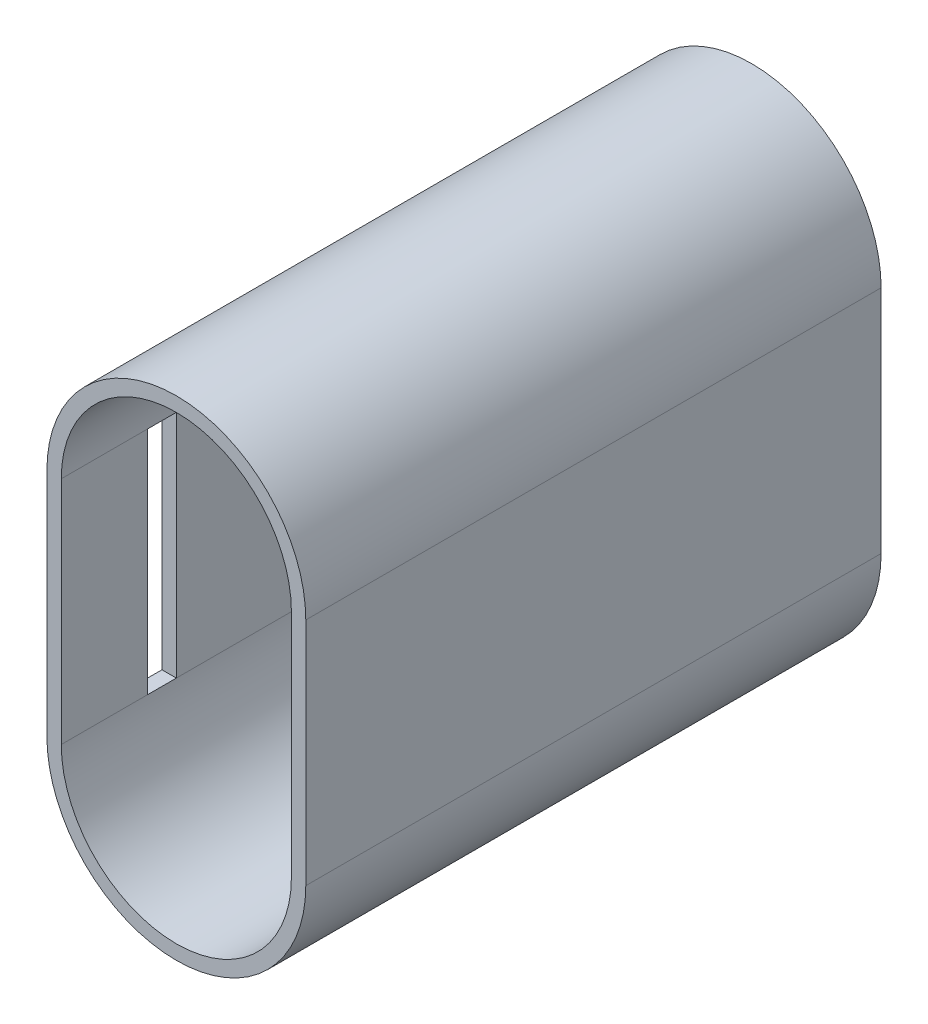
SolidWorks part; units mm, degrees
material "AISI 316 Нержавеющая сталь, лист (SS)"
ref_plane "Спереди" through (0, 0, 0) normal (0, 0, 1) x (1, 0, 0)
ref_plane "Сверху" through (0, 0, 0) normal (0, 1, 0) x (1, 0, 0)
ref_plane "Справа" through (0, 0, 0) normal (1, 0, 0) x (0, 0, -1)
other "Configuration Table"
sketch "Эскиз1" plane through (0, 0, 0) normal (0, 0, 1) x (1, 0, 0)
  line L0 (0, -40) -> (0, 40) construction
  line L1 (-45, -40) -> (-45, 40)
  line L2 (-40, -40) -> (-40, 40)
  line L3 (40, -40) -> (40, 40)
  line L4 (45, -40) -> (45, 40)
  arc A0 (-40, -40) -> (40, -40) centre (0, -40) ccw
  arc A1 (40, 40) -> (-40, 40) centre (0, 40) ccw
  arc A2 (45, 40) -> (-45, 40) centre (0, 40) ccw
  arc A3 (-45, -40) -> (45, -40) centre (0, -40) ccw
  point P3 (0, 80)
  point P4 (0, -80)
  point P5 (0, 0)
  dimension "D2" = 80
  dimension "D1" = 160
  dimension "D3" = 5
extrude "длина_камеры" add sketch "Эскиз1" along normal blind 200
sketch "Эскиз2" plane through (-45, 0, 0) normal (-1, 0, 0) x (0, 0, 1)
  line L0 (100, 40) -> (100, -40) construction
  line L1 (200, 40) -> (0, 40) construction
  line L2 (200, -40) -> (0, -40) construction
  line L4 (43, 40) -> (30, 40)
  line L5 (43, 40) -> (43, -40)
  line L6 (43, -40) -> (30, -40)
  line L7 (30, 40) -> (30, -40)
  line M6 (0, -40) -> (200, -40)
  line M8 (200, 40) -> (0, 40)
  dimension "D1" = 13
  dimension "D2" = 70
extrude "выпуск" cut sketch "Эскиз2" against normal up to surface and the other way through all contours L7 L5 M8 M6 up to face at (-40, 0, 100)
sketch "Эскиз3" plane through (-45, 0, 0) normal (-1, 0, 0) x (0, 0, 1)
  line L0 (0, 40) -> (200, 40) construction
  line L1 (100, 40) -> (100, -40) construction
  line L2 (200, -40) -> (43, -40) construction
  line L4 (160, 40) -> (170, 40)
  line L5 (160, 40) -> (160, -40)
  line L6 (160, -40) -> (170, -40)
  line L7 (170, 40) -> (170, -40)
  line M6 (43, -40) -> (200, -40)
  line M8 (200, 40) -> (43, 40)
  dimension "D1" = 70
  dimension "D2" = 10
extrude "впуск" cut sketch "Эскиз3" along direction (1, 0, 0) on the side against the normal up to surface (5 mm away) contours L7 L5 M8 M6
